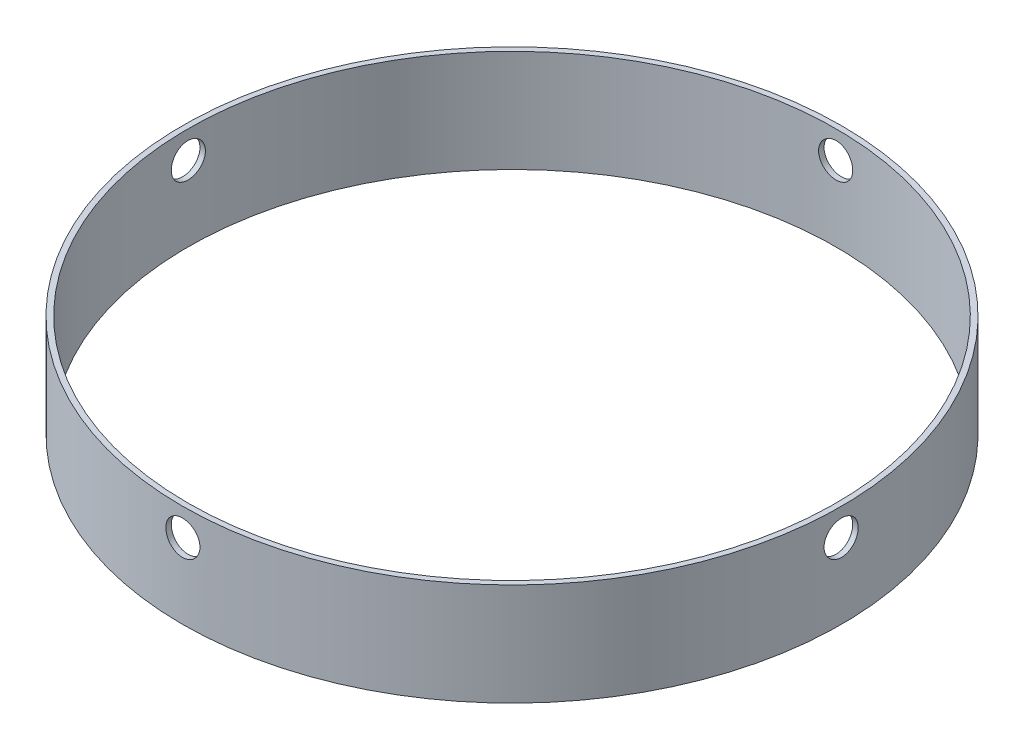
SolidWorks part; units mm, degrees
material "Stainless Steel (ferritic)"
ref_plane "Front Plane" through (0, 0, 0) normal (0, 0, 1) x (1, 0, 0)
ref_plane "Top Plane" through (0, 0, 0) normal (0, 1, 0) x (1, 0, 0)
ref_plane "Right Plane" through (0, 0, 0) normal (1, 0, 0) x (0, 0, -1)
sketch "Sketch1" plane through (0, 0, 0) normal (0, 1, 0) x (1, 0, 0)
  circle A0 centre (0, 0) radius 47.5
  circle A1 centre (0, 0) radius 48.3
  dimension "D2" = 95
  dimension "D1" = 0.8
extrude "Boss-Extrude1" add sketch "Sketch1" along normal blind 15
sketch "Sketch2" plane through (0, 0, 0) normal (0, 0, 1) x (1, 0, 0)
  line L2 (47.5, 15) -> (-47.5, 15) construction
  circle A0 centre (0, 11) radius 2.5
  dimension "D1" = 5
  dimension "D2" = 1.5
extrude "Cut-Extrude1" cut sketch "Sketch2" against normal through all both and the other way through all
sketch "Sketch3" plane through (0, 0, 0) normal (1, 0, 0) x (0, 0, -1)
  line L3 (47.5, 15) -> (-47.5, 15) construction
  circle A0 centre (0, 11) radius 2.5
  dimension "D1" = 5
  dimension "D2" = 1.5
extrude "Cut-Extrude2" cut sketch "Sketch3" against normal through all both and the other way through all
